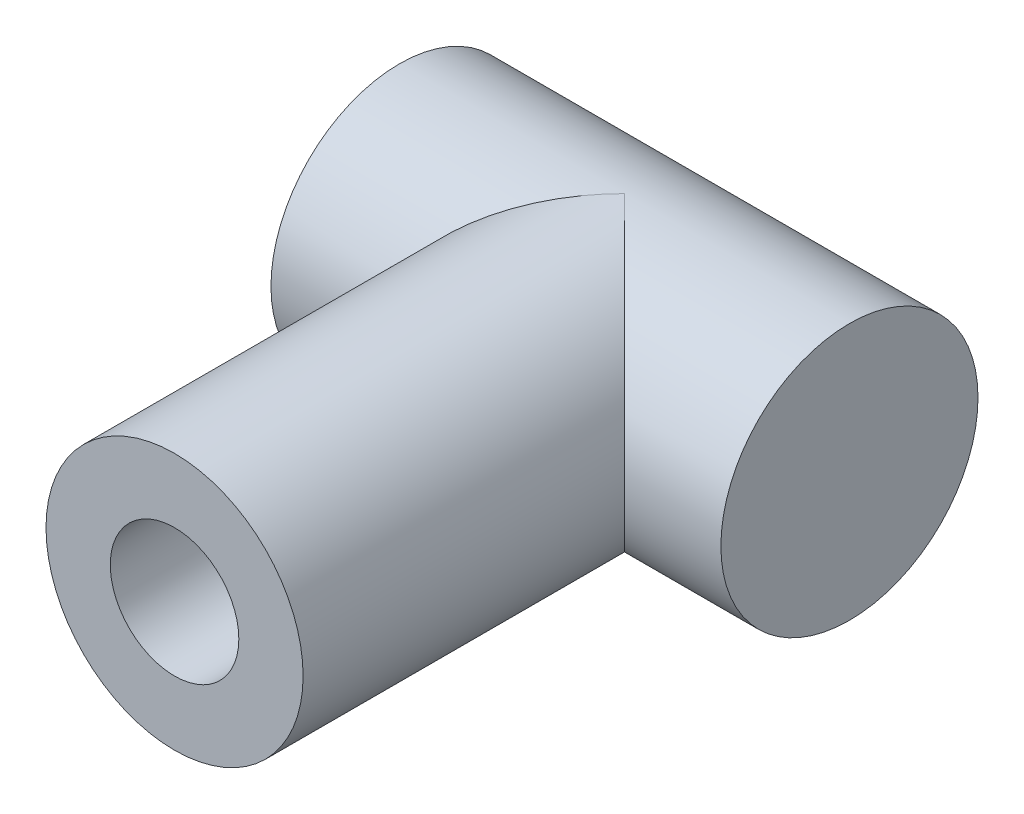
SolidWorks part; units mm, degrees
ref_plane "up基准面" through (0, 0, 0) normal (0, 0, 1) x (1, 0, 0)
ref_plane "前基准面" through (0, 0, 0) normal (0, 1, 0) x (1, 0, 0)
ref_plane "右视基准面" through (0, 0, 0) normal (1, 0, 0) x (0, 0, -1)
sketch "草图22" plane through (0, 0, 0) normal (1, 0, 0) x (0, 0, -1)
  circle A0 centre (0, 0) radius 10
extrude "凸台-拉伸12" add sketch "草图22" along normal mid plane 35
sketch "草图25" plane through (0, 0, 0) normal (0, 0, 1) x (1, 0, 0)
  circle A0 centre (0, 0) radius 10
extrude "凸台-拉伸13" add sketch "草图25" along normal blind 35
sketch "草图26" plane through (0, 0, 35) normal (0, 0, 1) x (1, 0, 0)
  circle A0 centre (0, 0) radius 5
extrude "切除-拉伸6" cut sketch "草图26" against normal blind 12
